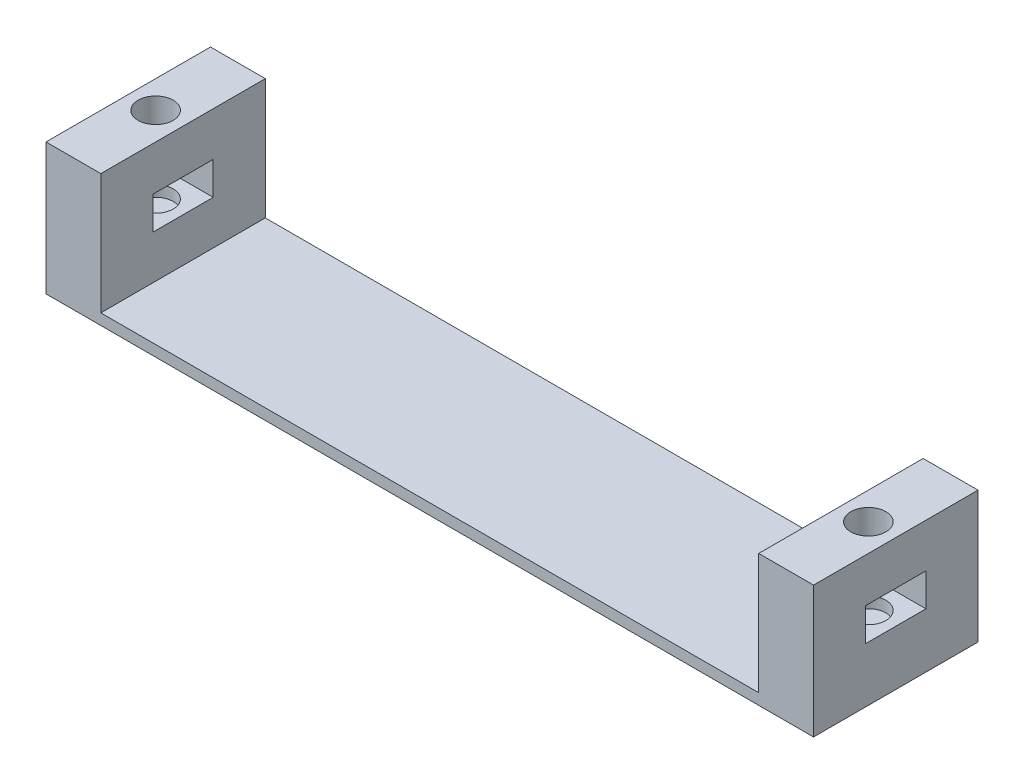
SolidWorks part; units mm, degrees
ref_plane "Front Plane" through (0, 0, 0) normal (0, 0, 1) x (1, 0, 0)
ref_plane "Top Plane" through (0, 0, 0) normal (0, 1, 0) x (1, 0, 0)
ref_plane "Right Plane" through (0, 0, 0) normal (1, 0, 0) x (0, 0, -1)
sketch "Sketch1" plane through (0, 0, 0) normal (0, 1, 0) x (1, 0, 0)
  line L1 (-35, -7.5) -> (35, -7.5)
  line L2 (-35, -7.5) -> (-35, 7.5)
  line L3 (-35, 7.5) -> (35, 7.5)
  line L4 (35, -7.5) -> (35, 7.5)
  line L5 (-35, -7.5) -> (35, 7.5) construction
  line L6 (-35, 7.5) -> (35, -7.5) construction
  point P0 (0, 0)
  dimension "D1" = 15
  dimension "D2" = 70
extrude "Boss-Extrude1" add sketch "Sketch1" along normal blind 1
sketch "Sketch2" plane through (0, 1, 0) normal (0, 1, 0) x (1, 0, 0)
  line L0 (-35, 7.5) -> (-30, 7.5)
  line L1 (35, 7.5) -> (-35, 7.5) construction
  line L2 (-30, 7.5) -> (-30, -7.5)
  line L3 (-35, -7.5) -> (35, -7.5) construction
  line L4 (-30, -7.5) -> (-35, -7.5)
  line L5 (-35, -7.5) -> (-35, 7.5)
  line L6 (35, 7.5) -> (35, -7.5)
  line L7 (35, -7.5) -> (35, 7.5) construction
  line L8 (35, -7.5) -> (30, -7.5)
  line L9 (30, -7.5) -> (30, 7.5)
  line L10 (30, 7.5) -> (35, 7.5)
  dimension "D1" = 5
  dimension "D2" = 5
extrude "Boss-Extrude2" add sketch "Sketch2" along normal blind 11
sketch "Sketch3" plane through (0, 12, 0) normal (0, 1, 0) x (1, 0, 0)
  line L0 (-35, 7.5) -> (-30, -7.5) construction
  line L1 (0, 7.5) -> (0, 0) construction
  line L2 (30, 7.5) -> (-30, 7.5) construction
  circle A0 centre (-32.5, 0) radius 1.6
  circle A1 centre (32.5, 0) radius 1.6
  dimension "D1" = 3.2
extrude "Cut-Extrude1" cut sketch "Sketch3" against normal blind 8
sketch "Sketch4" plane through (35, 0, 0) normal (1, 0, 0) x (0, 0, -1)
  line L0 (0, 12) -> (0, 0) construction
  line L1 (-7.5, 12) -> (7.5, 12) construction
  line L2 (2.75, 5) -> (-2.75, 5)
  line L3 (-2.75, 5) -> (-2.75, 8)
  line L4 (-2.75, 8) -> (2.75, 8)
  line L5 (2.75, 5) -> (2.75, 8)
  point P10 (0, 8)
  point P11 (0, 5)
  dimension "D1" = 3
  dimension "D2" = 5.5
  dimension "D3" = 4
extrude "Cut-Extrude2" cut sketch "Sketch4" against normal through all
